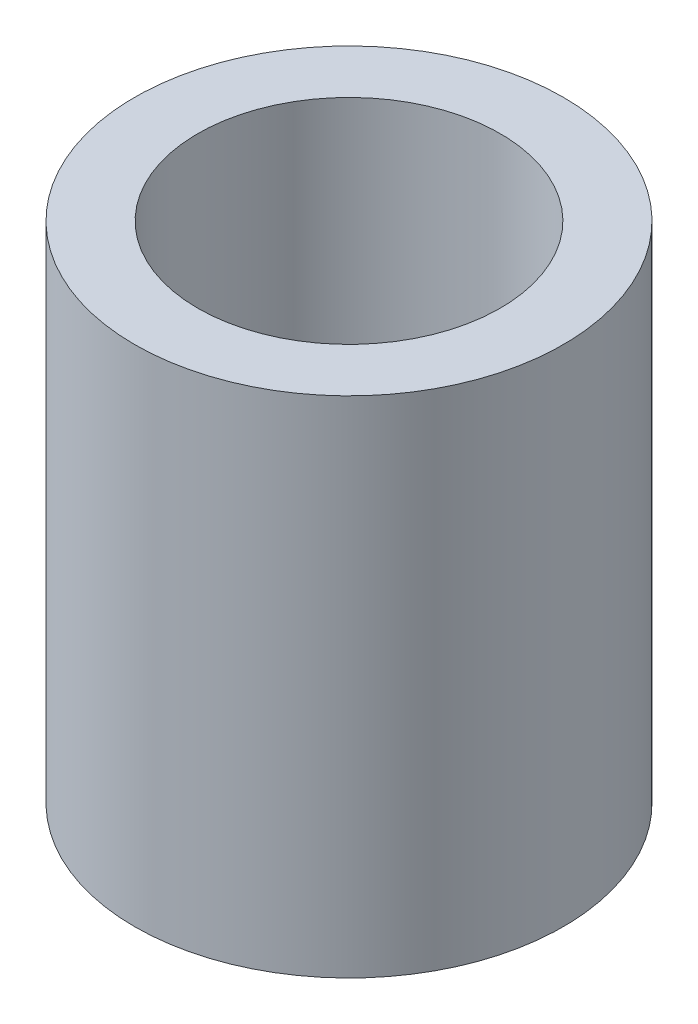
SolidWorks part; units mm, degrees
ref_plane "Front" through (0, 0, 0) normal (0, 0, 1) x (1, 0, 0)
ref_plane "Top" through (0, 0, 0) normal (0, 1, 0) x (1, 0, 0)
ref_plane "Right" through (0, 0, 0) normal (1, 0, 0) x (0, 0, -1)
sketch "Sketch2" plane through (0, 0, 0) normal (0, 1, 0) x (1, 0, 0)
  circle A0 centre (0, 0) radius 6
  circle A1 centre (0, 0) radius 8.5
  dimension "D1" = 12
  dimension "D2" = 17
extrude "Boss-Extrude1" add sketch "Sketch2" along normal blind 20
